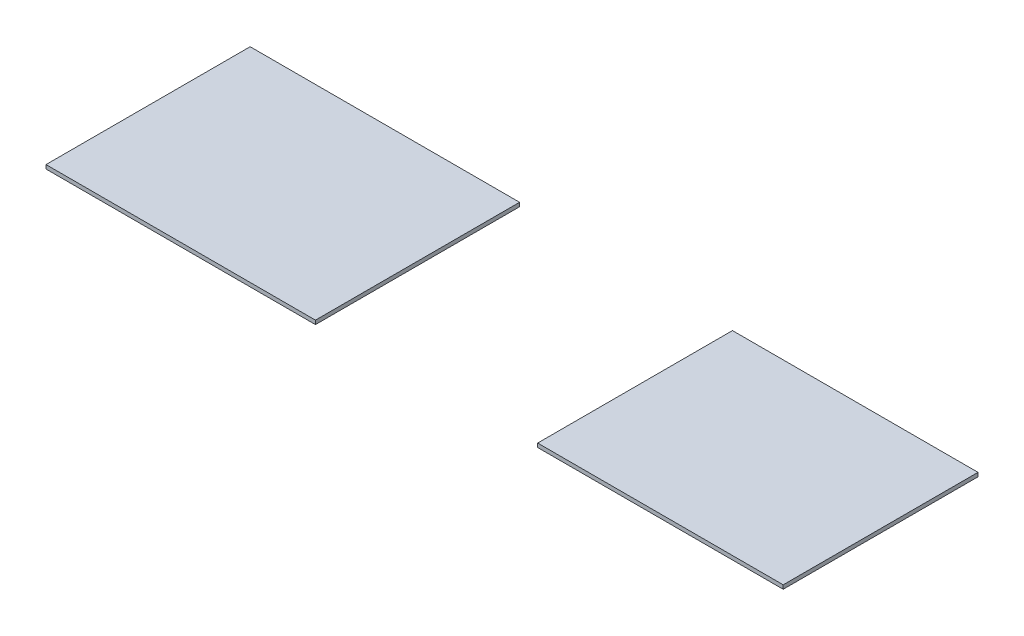
SolidWorks part; units mm, degrees
material "AISI 304"
ref_plane "Front Plane" through (0, 0, 0) normal (0, 0, 1) x (1, 0, 0)
ref_plane "Top Plane" through (0, 0, 0) normal (0, 1, 0) x (1, 0, 0)
ref_plane "Right Plane" through (0, 0, 0) normal (1, 0, 0) x (0, 0, -1)
sketch "Sketch1" plane through (0, 0, 0) normal (0, 1, 0) x (1, 0, 0)
  line L1 (118.3997, -22.8678) -> (519.539, -22.8678)
  line L2 (118.3997, -22.8678) -> (118.3997, 295.3757)
  line L3 (118.3997, 295.3757) -> (519.539, 295.3757)
  line L4 (519.539, -22.8678) -> (519.539, 295.3757)
  line L5 (118.3997, -22.8678) -> (519.539, 295.3757) construction
  line L6 (118.3997, 295.3757) -> (519.539, -22.8678) construction
  line L7 (-237.0039, -30.4904) -> (-677.209, -30.4904)
  line L8 (-237.0039, -30.4904) -> (-237.0039, 302.9983)
  line L9 (-237.0039, 302.9983) -> (-677.209, 302.9983)
  line L10 (-677.209, -30.4904) -> (-677.209, 302.9983)
  line L11 (-237.0039, -30.4904) -> (-677.209, 302.9983) construction
  line L12 (-237.0039, 302.9983) -> (-677.209, -30.4904) construction
  point P4 (318.9693, 136.2539)
  point P9 (-457.1065, 136.2539)
extrude "Boss-Extrude1" add sketch "Sketch1" along normal blind 6.35
